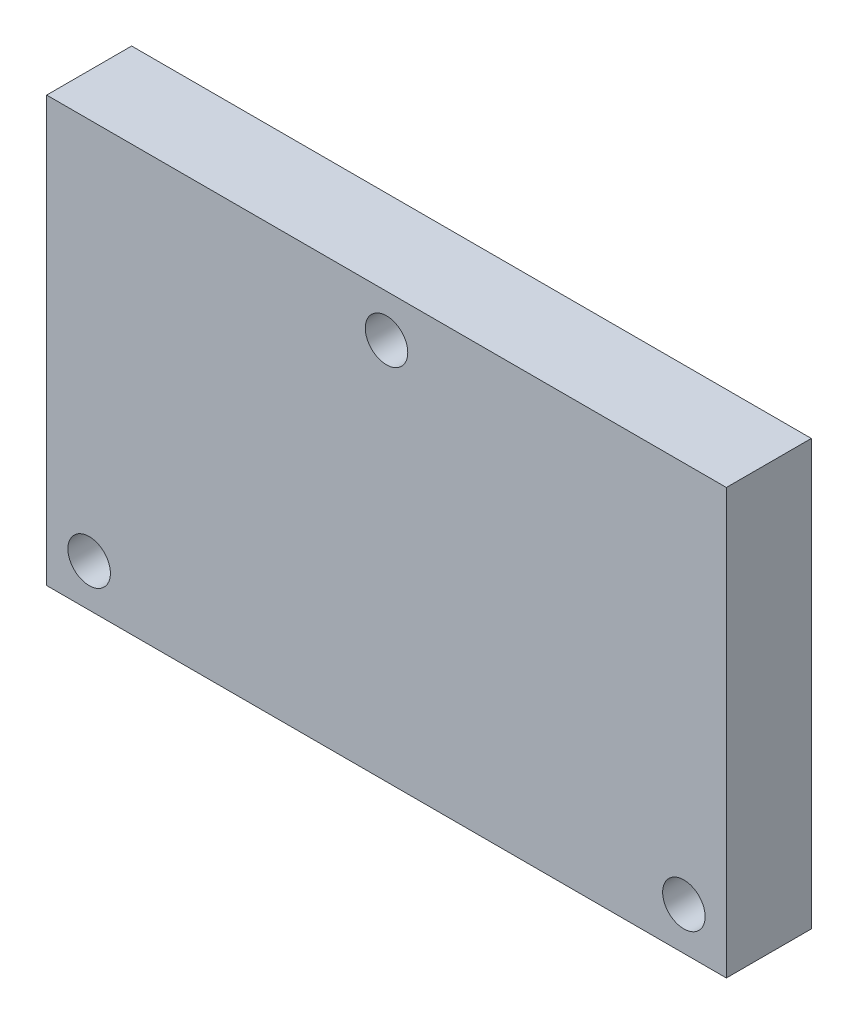
SolidWorks part; units mm, degrees
ref_plane "Спереди" through (0, 0, 0) normal (0, 0, 1) x (1, 0, 0)
ref_plane "Сверху" through (0, 0, 0) normal (0, 1, 0) x (1, 0, 0)
ref_plane "Справа" through (0, 0, 0) normal (1, 0, 0) x (0, 0, -1)
sketch "Эскиз1" plane through (0, 0, 0) normal (0, 0, 1) x (1, 0, 0)
  line L0 (-68.25, -336) -> (-68.25, -366)
  line L1 (-72.5875, -336) -> (-67.6875, -336) construction
  line L2 (-72.5875, -366) -> (-67.6875, -366) construction
  line L3 (-68.25, -366) -> (-20.25, -366)
  line L4 (-20.8625, -366) -> (-10.8625, -366) construction
  line L5 (-68.25, -336) -> (-20.25, -336)
  line L6 (-67.6875, -336) -> (-20.8625, -336) construction
  line L7 (-44.25, -339) -> (-44.25, -50339) construction
  line L8 (-20.25, -336) -> (-20.25, -366)
  circle A0 centre (-65.25, -363) radius 1.5 construction
  circle A1 centre (-23.25, -363) radius 1.5 construction
  circle A2 centre (-44.25, -339) radius 1.5 construction
  circle A3 centre (-65.25, -363) radius 1.5
  circle A4 centre (-23.25, -363) radius 1.5
  circle A5 centre (-44.25, -339) radius 1.5
  point P19 (-17.8556, -366)
  point P25 (0, 0)
  dimension "D1" = 3
extrude "Бобышка-Вытянуть1" add sketch "Эскиз1" along normal blind 6
